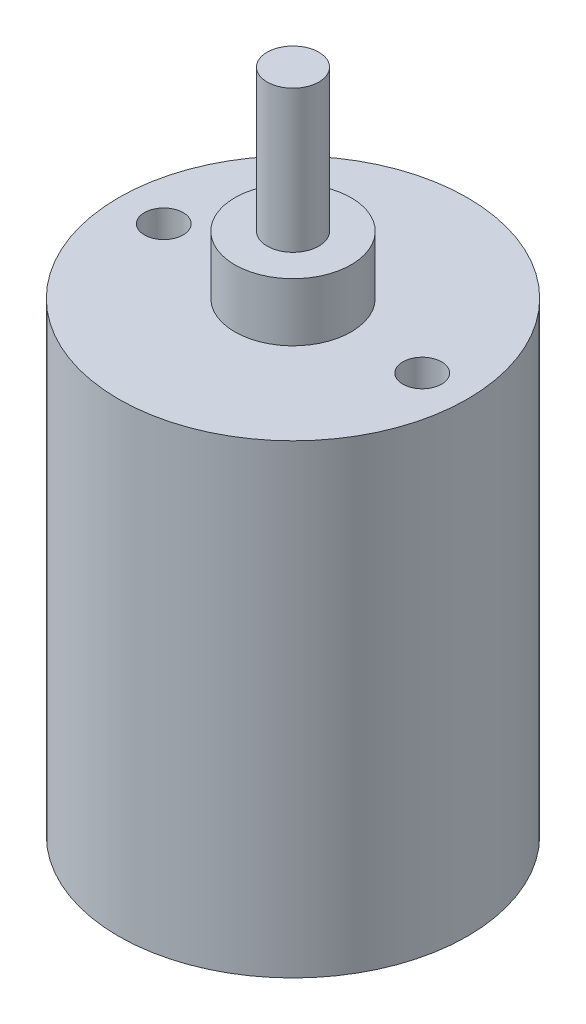
SolidWorks part; units mm, degrees
ref_plane "Plan de face" through (0, 0, 0) normal (0, 0, 1) x (1, 0, 0)
ref_plane "Plan de dessus" through (0, 0, 0) normal (0, 1, 0) x (1, 0, 0)
ref_plane "Plan de droite" through (0, 0, 0) normal (1, 0, 0) x (0, 0, -1)
sketch "Esquisse1" plane through (0, 0, 0) normal (0, 1, 0) x (1, 0, 0)
  circle A0 centre (0, 0) radius 4.25
extrude "Extrusion1" add sketch "Esquisse1" along normal blind 1
sketch "Esquisse2" plane through (0, 1, 0) normal (0, 1, 0) x (-1, 0, 0)
  circle A0 centre (0, 0) radius 13.5
extrude "Extrusion2" add sketch "Esquisse2" along normal blind 36
sketch "Esquisse3" plane through (0, 37, 0) normal (0, 1, 0) x (-1, 0, 0)
  circle A0 centre (0, 0) radius 4.5
extrude "Extrusion3" add sketch "Esquisse3" along normal blind 4.5
sketch "Esquisse4" plane through (0, 41.5, 0) normal (0, 1, 0) x (-1, 0, 0)
  circle A0 centre (0, 0) radius 2
extrude "Extrusion4" add sketch "Esquisse4" along normal blind 11
sketch "Esquisse5" plane through (0, 37, 0) normal (0, 1, 0) x (1, 0, 0)
  circle A0 centre (10, 0) radius 1.5
  circle A1 centre (0, 0) radius 10 construction
  circle A2 centre (-10, 0) radius 1.5
extrude "Extrusion5" cut sketch "Esquisse5" against normal blind 4
